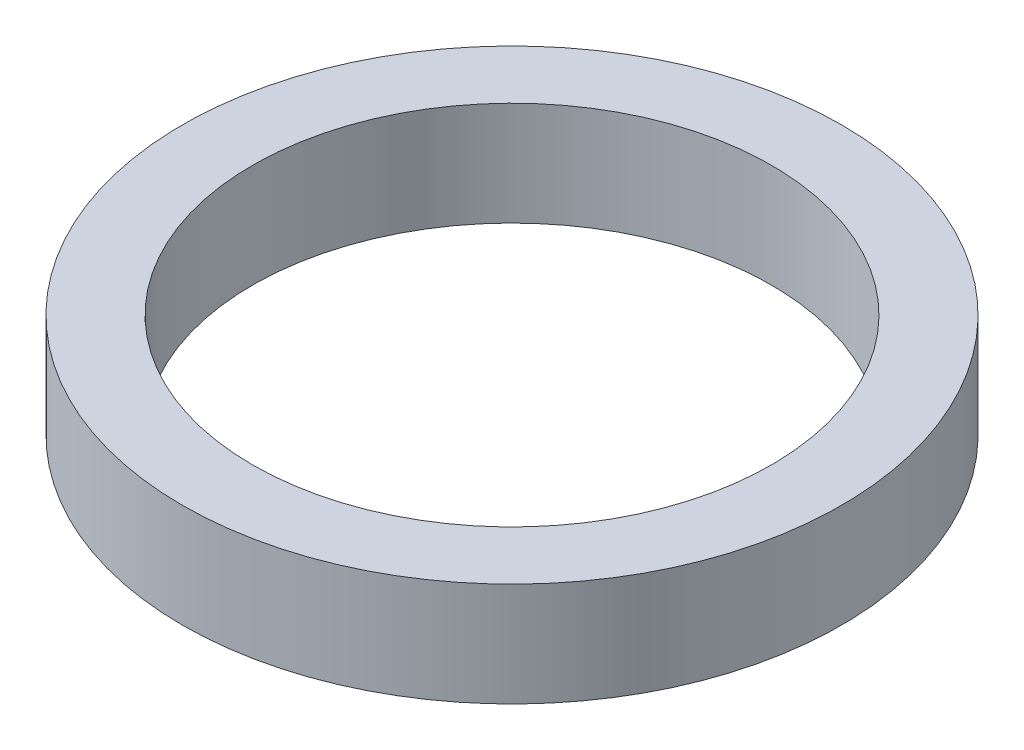
SolidWorks part; units mm, degrees
ref_plane "Alzado" through (0, 0, 0) normal (0, 0, 1) x (1, 0, 0)
ref_plane "Planta" through (0, 0, 0) normal (0, 1, 0) x (1, 0, 0)
ref_plane "Vista lateral" through (0, 0, 0) normal (1, 0, 0) x (0, 0, -1)
sketch "Croquis1" plane through (0, 0, 0) normal (0, 1, 0) x (1, 0, 0)
  circle A0 centre (0, 0) radius 5
  circle A1 centre (0, 0) radius 6.35
  dimension "D1" = 12.7
  dimension "D2" = 10
extrude "Saliente-Extruir1" add sketch "Croquis1" along normal blind 2
